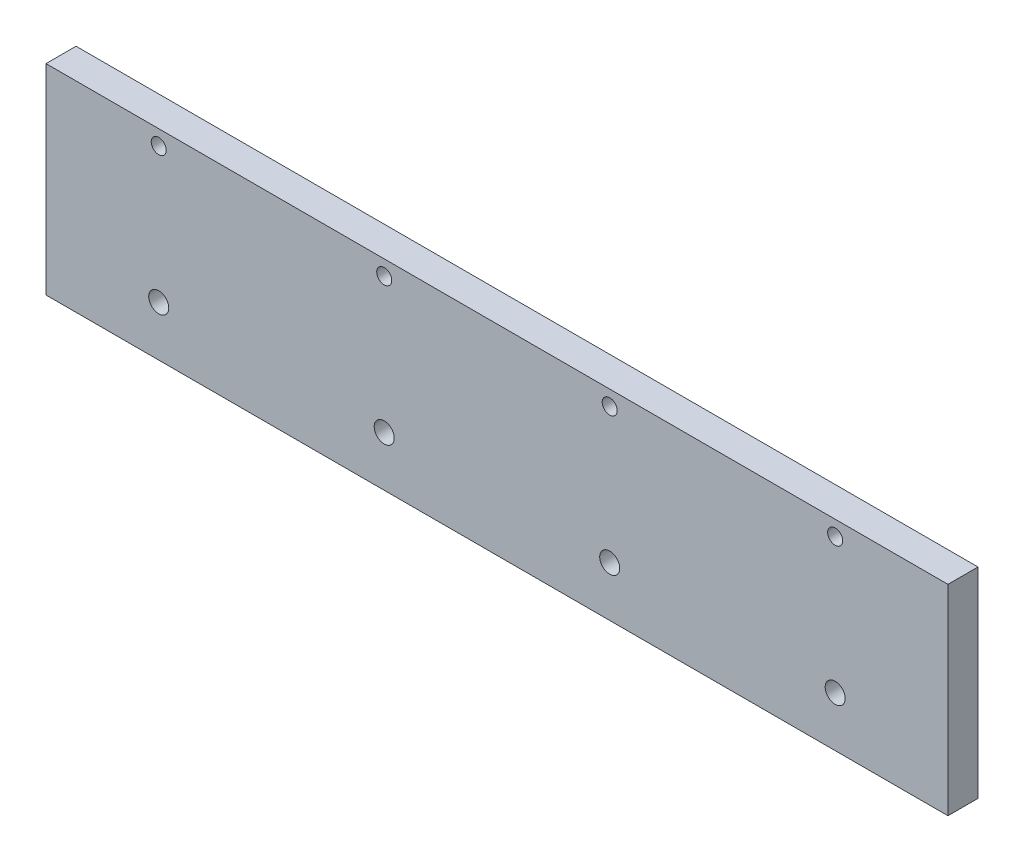
SolidWorks part; units mm, degrees
material "Beech"
ref_plane "Front Plane" through (0, 0, 0) normal (0, 0, 1) x (1, 0, 0)
ref_plane "Top Plane" through (0, 0, 0) normal (0, 1, 0) x (1, 0, 0)
ref_plane "Right Plane" through (0, 0, 0) normal (1, 0, 0) x (0, 0, -1)
sketch "Sketch1" plane through (0, 0, 0) normal (0, 0, 1) x (1, 0, 0)
  line L1 (-180, -40) -> (180, -40)
  line L2 (-180, -40) -> (-180, 40)
  line L3 (-180, 40) -> (180, 40)
  line L4 (180, -40) -> (180, 40)
  line L5 (-180, -40) -> (180, 40) construction
  line L6 (-180, 40) -> (180, -40) construction
  point P0 (0, 0)
extrude "Boss-Extrude1" add sketch "Sketch1" along normal blind 12
sketch "Sketch2" plane through (0, 0, 12) normal (0, 0, 1) x (1, 0, 0)
  line L0 (-180, 40) -> (-180, -40) construction
  line L1 (180, 40) -> (-180, 40) construction
  line L2 (-180, -40) -> (180, -40) construction
  circle A0 centre (-135, 34) radius 3
  circle A1 centre (-135, -20) radius 4
  dimension "D1" = 6
  dimension "D2" = 45
  dimension "D3" = 6
  dimension "D4" = 8
  dimension "D5" = 45
  dimension "D6" = 20
extrude "Cut-Extrude1" cut sketch "Sketch2" against normal up to next
pattern_linear "LPattern1" count 4 spacing 90 along (1, 0, 0) of "Cut-Extrude1"
